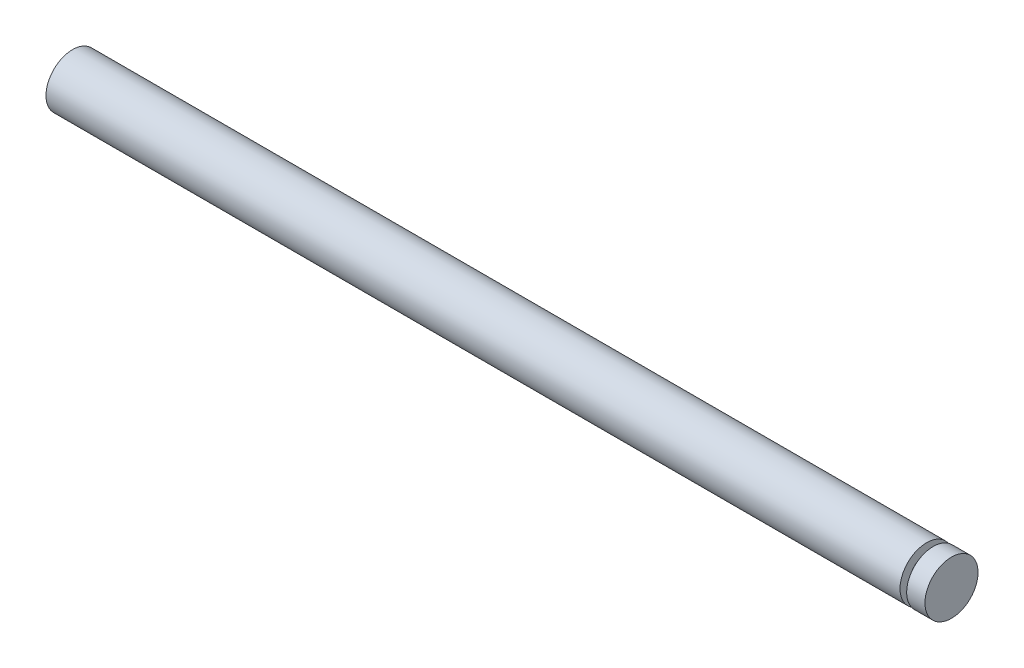
SolidWorks part; units mm, degrees
ref_plane "Front Plane" through (0, 0, 0) normal (0, 0, 1) x (1, 0, 0)
ref_plane "Top Plane" through (0, 0, 0) normal (0, 1, 0) x (1, 0, 0)
ref_plane "Right Plane" through (0, 0, 0) normal (1, 0, 0) x (0, 0, -1)
sketch "Sketch1" plane through (0, 0, 0) normal (1, 0, 0) x (0, 0, -1)
  circle A0 centre (0, 0) radius 18.415
  dimension "D1" = 36.83
extrude "Boss-Extrude1" add sketch "Sketch1" along normal blind 609.6
sketch "Sketch2" plane through (0, 0, 0) normal (0, 0, 1) x (1, 0, 0)
  line L0 (609.6, 18.415) -> (0, 18.415) construction
  line L1 (592.328, 18.415) -> (596.9, 18.415)
  line L2 (592.328, 18.415) -> (592.328, 12.065)
  line L3 (592.328, 12.065) -> (596.9, 12.065)
  line L4 (596.9, 18.415) -> (596.9, 12.065)
  line L5 (609.6, -18.415) -> (609.6, 18.415) construction
  line L6 (611.9158, 0) -> (517.6528, 0) construction
  dimension "D1" = 6.35
  dimension "D2" = 4.572
  dimension "D3" = 12.7
revolve "Cut-Revolve1" cut sketch "Sketch2" angle 360 about L6
